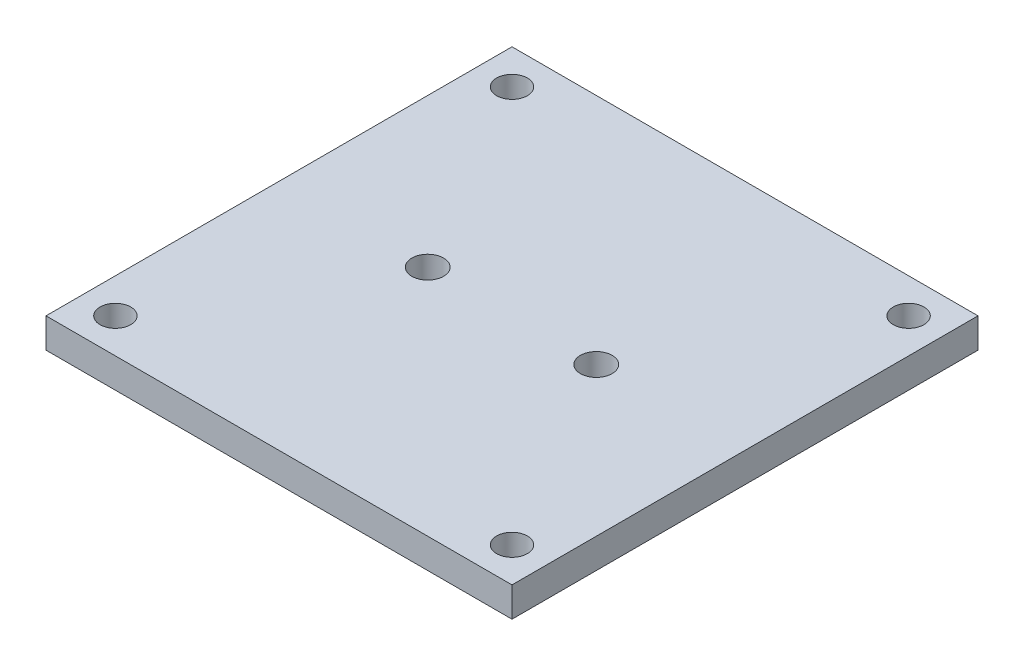
SolidWorks part; units mm, degrees
ref_plane "前视基准面" through (0, 0, 0) normal (0, 0, 1) x (1, 0, 0)
ref_plane "上视基准面" through (0, 0, 0) normal (0, 1, 0) x (1, 0, 0)
ref_plane "右视基准面" through (0, 0, 0) normal (1, 0, 0) x (0, 0, -1)
sketch "草图1" plane through (0, 0, 0) normal (0, 1, 0) x (1, 0, 0)
  line L1 (-23.5, 23.5) -> (23.5, 23.5)
  line L2 (-23.5, 23.5) -> (-23.5, -23.5)
  line L3 (-23.5, -23.5) -> (23.5, -23.5)
  line L4 (23.5, 23.5) -> (23.5, -23.5)
  line L5 (-23.5, 23.5) -> (23.5, -23.5) construction
  line L6 (-23.5, -23.5) -> (23.5, 23.5) construction
  point P0 (0, 0)
  dimension "D1" = 47
  dimension "D2" = 47
extrude "凸台-拉伸1" add sketch "草图1" along normal blind 3
sketch "草图3" plane through (0, 0, 0) normal (0, -1, 0) x (1, 0, 0)
  line L0 (-20, 0) -> (20, 0) construction
  line L1 (-20, 20) -> (20, 20) construction
  line L2 (-20, 20) -> (-20, -20) construction
  line L3 (-20, -20) -> (20, -20) construction
  line L4 (20, 20) -> (20, -20) construction
  line L5 (-20, 20) -> (20, -20) construction
  line L6 (-20, -20) -> (20, 20) construction
  line L7 (0, 20) -> (0, -20) construction
  circle A0 centre (20, 20) radius 1.55
  circle A1 centre (-20, 20) radius 1.55
  circle A2 centre (20, -20) radius 1.55
  circle A3 centre (-20, -20) radius 1.55
  point P0 (0, 0)
  dimension "D3" = 3.1
  dimension "D1" = 40
  dimension "D2" = 40
extrude "切除-拉伸2" cut sketch "草图3" against normal blind 3
sketch "草图4" plane through (0, 3, 0) normal (0, 1, 0) x (1, 0, 0)
  line L0 (-23.5, 0) -> (23.5, 0) construction
  line L1 (-23.5, 23.5) -> (-23.5, -23.5) construction
  line L2 (23.5, -23.5) -> (23.5, 23.5) construction
  line L3 (0, 23.5) -> (0, -23.5) construction
  line L4 (23.5, 23.5) -> (-23.5, 23.5) construction
  line L5 (-23.5, -23.5) -> (23.5, -23.5) construction
  circle A0 centre (-8.5, 0) radius 1.6
  circle A1 centre (8.5, 0) radius 1.6
  dimension "D1" = 3.2
  dimension "D2" = 8.5
extrude "切除-拉伸3" cut sketch "草图4" against normal blind 3
